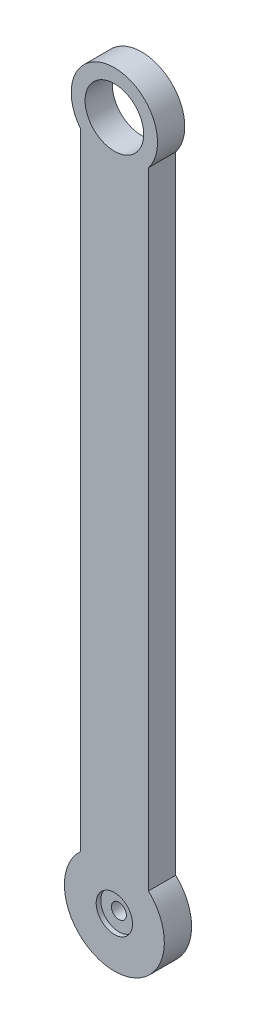
SolidWorks part; units mm, degrees
ref_plane "Plan de face" through (0, 0, 0) normal (0, 0, 1) x (1, 0, 0)
ref_plane "Plan de dessus" through (0, 0, 0) normal (0, 1, 0) x (1, 0, 0)
ref_plane "Plan de droite" through (0, 0, 0) normal (1, 0, 0) x (0, 0, -1)
sketch "Esquisse1" plane through (0, 0, 0) normal (0, 0, 1) x (1, 0, 0)
  line L1 (0, 0) -> (15, 0)
  line L2 (0, 0) -> (0, 165)
  line L3 (0, 165) -> (15, 165)
  line L4 (15, 0) -> (15, 165)
  dimension "D1" = 165
  dimension "D2" = 15
extrude "Boss.-Extru.1" add sketch "Esquisse1" along normal blind 6
sketch "Esquisse2" plane through (0, 0, 6) normal (0, 0, 1) x (1, 0, 0)
  line L0 (15, 0) -> (15, 165) construction
  line L1 (0, 0) -> (15, 0) construction
  line L2 (15, 165) -> (0, 165) construction
  line L3 (15, 0) -> (15, 165) construction
  circle A0 centre (7.5, 7.5) radius 11
  circle A1 centre (7.5, 159.25) radius 9.5
  dimension "D2" = 22
  dimension "D5" = 19
  dimension "D1" = 7.5
  dimension "D3" = 7.5
  dimension "D4" = 5.75
  dimension "D6" = 7.5
extrude "Boss.-Extru.2" add sketch "Esquisse2" against normal blind 6
sketch "Esquisse3" plane through (0, 0, 0) normal (0, 0, -1) x (-1, 0, 0)
  circle A0 centre (-7.5, 7.5) radius 1.65
  circle A1 centre (-7.5, 159.25) radius 6.45
  dimension "D1" = 3.3
  dimension "D2" = 12.9
extrude "Enlèv. mat.-Extru.1" cut sketch "Esquisse3" against normal blind 10
sketch "Esquisse4" plane through (0, 0, 6) normal (0, 0, 1) x (1, 0, 0)
  circle A0 centre (7.5, 7.5) radius 4
  dimension "D1" = 8
extrude "Enlèv. mat.-Extru.2" cut sketch "Esquisse4" against normal blind 1
